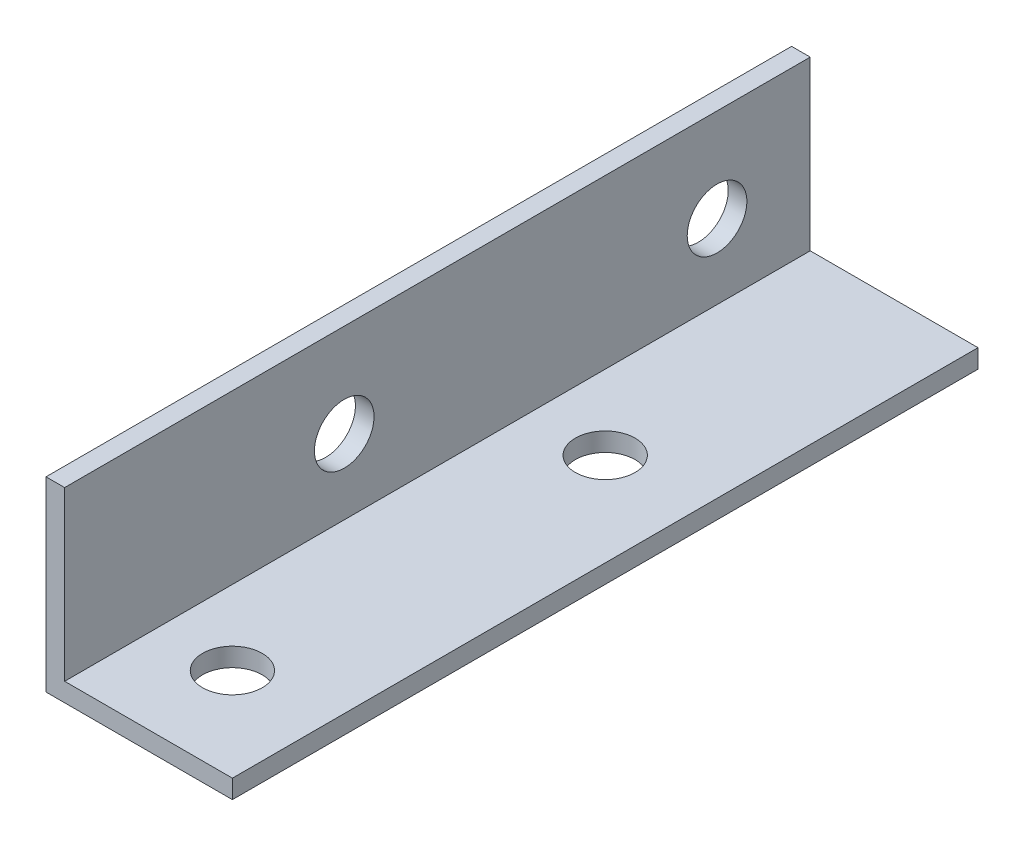
SolidWorks part; units mm, degrees
ref_plane "正面" through (0, 0, 0) normal (0, 0, 1) x (1, 0, 0)
ref_plane "平面" through (0, 0, 0) normal (0, 1, 0) x (1, 0, 0)
ref_plane "右側面" through (0, 0, 0) normal (1, 0, 0) x (0, 0, -1)
sketch "ｽｹｯﾁ1" plane through (0, 0, 0) normal (0, 0, 1) x (1, 0, 0)
  line L0 (-4, 5) -> (-4, -4)
  line L1 (5, -5) -> (-5, -5)
  line L2 (5, -5) -> (5, -4)
  line L3 (-4, 5) -> (-5, 5)
  line L4 (-5, -5) -> (-5, 5)
  line L5 (5, -5) -> (-5, 5) construction
  line L6 (5, 5) -> (-5, -5) construction
  line L7 (-4, -4) -> (5, -4)
  point P0 (0, 0)
  dimension "D1" = 10
  dimension "D2" = 1
  dimension "D3" = 10
  dimension "D4" = 1
extrude "ﾎﾞｽ - 押し出し1" add sketch "ｽｹｯﾁ1" along normal blind 40
sketch "ｽｹｯﾁ2" plane through (0, -5, 0) normal (0, -1, 0) x (1, 0, 0)
  line L0 (0, 0) -> (0, 40) construction
  line L1 (-5, 0) -> (5, 0) construction
  line L2 (-5, 40) -> (5, 40) construction
  line L3 (5, 40) -> (-4, 40) construction
  circle A1 centre (0, 15) radius 1.6
  circle A2 centre (0, 35) radius 1.6
  dimension "D1" = 20
  dimension "D2" = 5
  dimension "D3" = 3.2
extrude "ｶｯﾄ - 押し出し1" cut sketch "ｽｹｯﾁ2" against normal through all and the other way through all
sketch "ｽｹｯﾁ3" plane through (-5, 0, 0) normal (-1, 0, 0) x (0, 0, 1)
  line L0 (40, 0) -> (0, 0) construction
  line L1 (40, 5) -> (40, -5) construction
  line L2 (0, 5) -> (0, -5) construction
  line L3 (0, -4) -> (0, 5) construction
  circle A0 centre (5, 0) radius 1.6
  circle A1 centre (25, 0) radius 1.6
  dimension "D1" = 20
  dimension "D2" = 5
  dimension "D3" = 3.2
extrude "ｶｯﾄ - 押し出し2" cut sketch "ｽｹｯﾁ3" against normal through all
